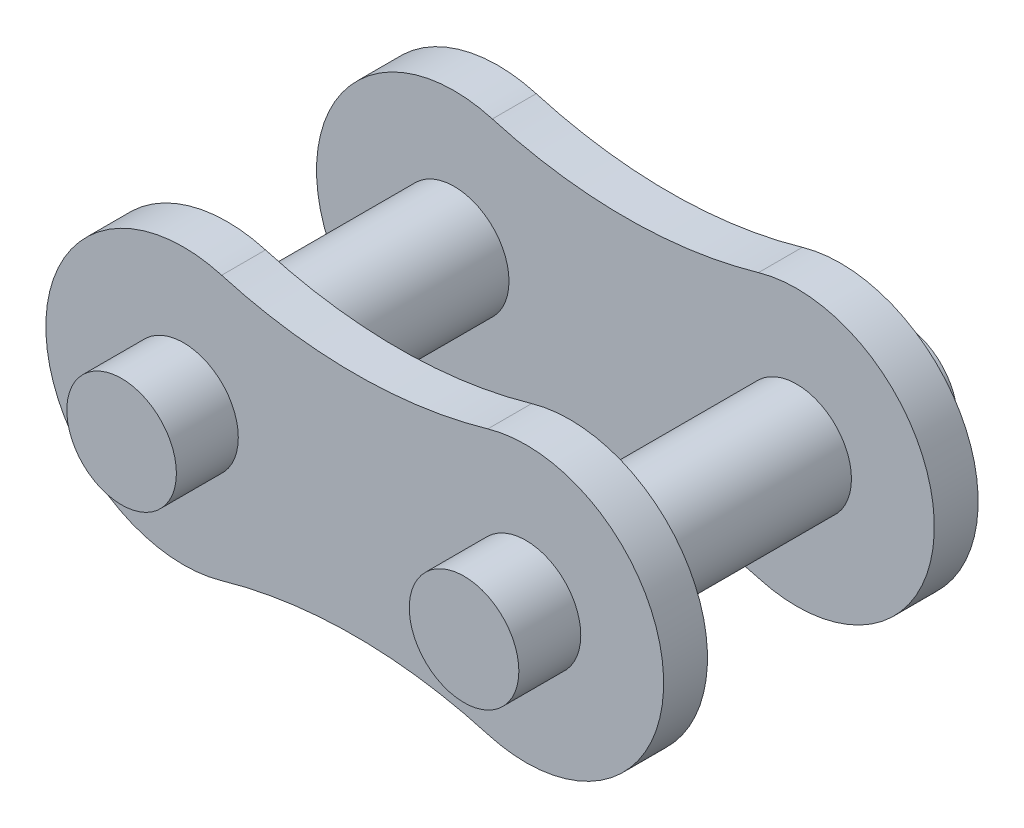
SolidWorks part; units mm, degrees
ref_plane "Front Plane" through (0, 0, 0) normal (0, 0, 1) x (1, 0, 0)
ref_plane "Top Plane" through (0, 0, 0) normal (0, 1, 0) x (1, 0, 0)
ref_plane "Right Plane" through (0, 0, 0) normal (1, 0, 0) x (0, 0, -1)
sketch "Sketch1" plane through (0, 0, 0) normal (0, 0, 1) x (1, 0, 0)
  line L0 (-7.9375, 0) -> (7.9375, 0) construction
  line L1 (-7.9375, 7.2517) -> (-7.9375, -7.2517) construction
  line L2 (0, -6.1639) -> (0, 6.1639) construction
  circle A0 centre (-7.9375, 0) radius 5.08
  circle A1 centre (7.9375, 0) radius 5.08
  circle A2 centre (-7.9375, 0) radius 2.54
  circle A3 centre (7.9375, 0) radius 2.54
  arc A4 (-5.9866, 6.9843) -> (-5.9866, -6.9843) centre (-7.9375, 0) ccw
  arc A5 (5.9866, -6.9843) -> (5.9866, 6.9843) centre (7.9375, 0) ccw
  arc A6 (-5.9866, 6.9843) -> (5.9866, 6.9843) centre (0, 28.4166) ccw
  arc A7 (-5.9866, -6.9843) -> (5.9866, -6.9843) centre (0, -28.4166) cw
  dimension "Roller Dia" = 10.16
  dimension "Pin Dia" = 5.08
  dimension "Pitch" = 15.875
  dimension "H" = 14.5034
  dimension "D2" = 12.3279
sketch "Sketch2" plane through (0, 0, 0) normal (0, 1, 0) x (1, 0, 0)
  line L0 (0, 3.175) -> (0, -3.175) construction
  point P2 (0, -5.207)
  point P4 (0, 5.207)
  point P5 (0, 5.2578)
  point P6 (0, 7.2898)
  dimension "W" = 6.35
  dimension "T" = 2.032
  dimension "D1" = 2.032
  dimension "D2" = 2.032
  dimension "D3" = 0.0508
ref_plane "Plane1" through (0, 0, 3.175) normal (0, 0, 1) x (1, 0, 0)
ref_plane "Plane2" through (0, 0, -5.2578) normal (0, 0, 1) x (1, 0, 0)
sketch "Sketch4" plane through (0, 0, 0) normal (0, 0, 1) x (1, 0, 0)
  circle A0 centre (-7.9375, 0) radius 5.08 construction
  circle A1 centre (-7.9375, 0) radius 5.08
  circle A2 centre (7.9375, 0) radius 5.08 construction
  circle A3 centre (7.9375, 0) radius 5.08
  circle A4 centre (-7.9375, 0) radius 2.5654
  circle A5 centre (7.9375, 0) radius 2.5654
  dimension "D1" = 5.1308
  dimension "D2" = 5.1308
extrude "Boss-Extrude1" add sketch "Sketch4" along normal mid plane 6.35
sketch "Sketch5" plane through (0, 0, 3.175) normal (0, 0, 1) x (1, 0, 0)
  arc A0 (-5.9866, 6.9843) -> (-5.9866, -6.9843) centre (-7.9375, 0) ccw construction
  arc A1 (-5.9866, 6.9843) -> (5.9866, 6.9843) centre (0, 28.4166) ccw construction
  circle A2 centre (-7.9375, 0) radius 2.54 construction
  arc A3 (5.9866, -6.9843) -> (5.9866, 6.9843) centre (7.9375, 0) ccw construction
  circle A4 centre (7.9375, 0) radius 2.54 construction
  arc A5 (5.9866, -6.9843) -> (-5.9866, -6.9843) centre (0, -28.4166) ccw construction
  arc A6 (-5.9866, 6.9843) -> (-5.9866, -6.9843) centre (-7.9375, 0) ccw
  arc A7 (-5.9866, 6.9843) -> (5.9866, 6.9843) centre (0, 28.4166) ccw
  circle A8 centre (-7.9375, 0) radius 2.54
  arc A9 (5.9866, -6.9843) -> (5.9866, 6.9843) centre (7.9375, 0) ccw
  circle A10 centre (7.9375, 0) radius 2.54
  arc A11 (5.9866, -6.9843) -> (-5.9866, -6.9843) centre (0, -28.4166) ccw
extrude "Boss-Extrude2" add sketch "Sketch5" along normal up to vertex (2.032 mm away) separate body up to point (0, 0, 5.207)
pattern_linear "LPattern1" count 2 spacing 15.875 along (1, 0, 0) of bodies 102
sketch "Sketch7" plane through (0, 0, -5.2578) normal (0, 0, 1) x (1, 0, 0)
  line L0 (23.8125, 6.3815) -> (23.8125, -6.3815) construction
  arc A0 (9.7065, 6.1314) -> (9.7065, -6.1314) centre (7.9375, 0) ccw
  arc A1 (22.0435, -6.1314) -> (22.0435, 6.1314) centre (23.8125, 0) ccw
  arc A2 (5.9866, -6.9843) -> (5.9866, 6.9843) centre (7.9375, 0) ccw construction
  circle A3 centre (23.8125, 0) radius 5.08 construction
  arc A4 (9.7065, 6.1314) -> (22.0435, 6.1314) centre (15.875, 27.5121) ccw
  arc A5 (9.7065, -6.1314) -> (22.0435, -6.1314) centre (15.875, -27.5121) cw
  arc A6 (-5.9866, 6.9843) -> (5.9866, 6.9843) centre (0, 28.4166) ccw construction
  circle A7 centre (7.9375, 0) radius 2.54 construction
  circle A8 centre (7.9375, 0) radius 2.54
  circle A9 centre (23.8125, 0) radius 2.54
  dimension "D2" = 12.763
extrude "Boss-Extrude3" add sketch "Sketch7" against normal up to vertex (2.032 mm away) separate body up to point (0, 0, -7.2898)
mirror "Mirror1" about plane through (0, 0, 0) normal (0, 0, 1) of bodies 103 105
sketch "Sketch8" plane through (0, 0, 0) normal (0, 0, 1) x (1, 0, 0)
  circle A0 centre (7.9375, 0) radius 2.54
  circle A1 centre (23.8125, 0) radius 2.54
  circle A2 centre (7.9375, 0) radius 2.54 construction
  circle A3 centre (23.8125, 0) radius 2.54 construction
extrude "Boss-Extrude4" add sketch "Sketch8" against normal blind 10.16 and the other way blind 10.16 separate body
delete or keep bodies "Body-Delete1" type delete bodies bodies 104
delete or keep bodies "Body-Delete/Keep 1" type delete bodies bodies 101 106 102 103
equation "\"D2@Sketch1\" =\"H@Sketch1\"*.85"
equation "\"D1@Sketch2\" = \"T@Sketch2\""
equation "\"D1@Sketch4\" = \"Pin Dia@Sketch1\"+.002"
equation "\"D2@Sketch4\" = \"D1@Sketch4\""
equation "\"D1@Boss-Extrude1\" = \"W@Sketch2\""
equation "\"D2@Sketch2\" = \"T@Sketch2\""
equation "\"D3@LPattern1\" = \"Pitch@Sketch1\""
equation "\"D2@Sketch7\" = \"H@Sketch1\"*.88"
